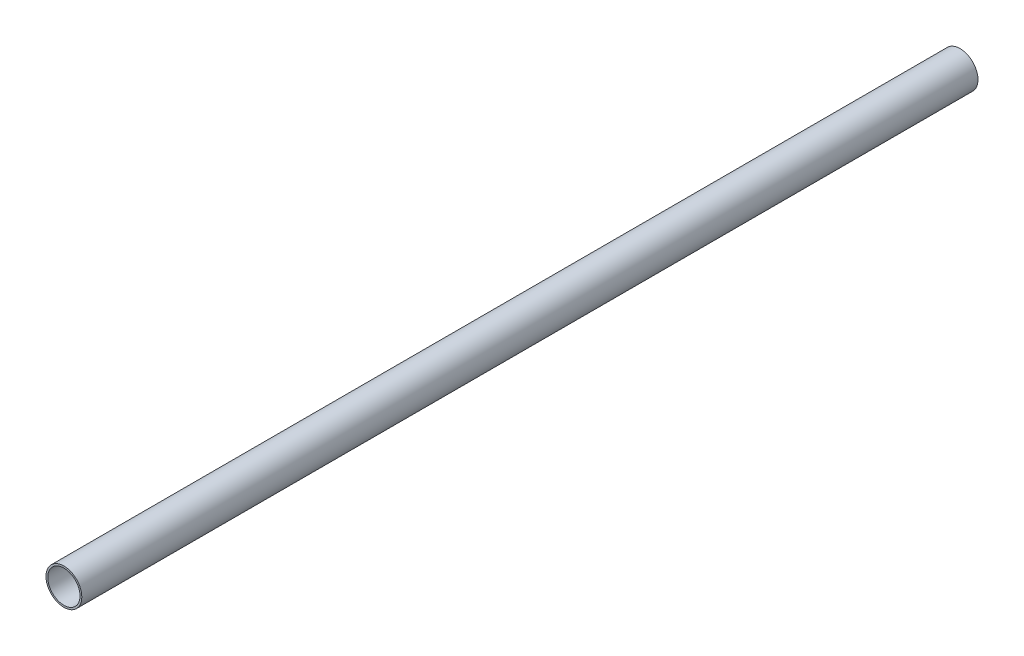
SolidWorks part; units mm, degrees
material "Thornel Mat VMA"
ref_plane "Front Plane" through (0, 0, 0) normal (0, 0, 1) x (1, 0, 0)
ref_plane "Top Plane" through (0, 0, 0) normal (0, 1, 0) x (1, 0, 0)
ref_plane "Right Plane" through (0, 0, 0) normal (1, 0, 0) x (0, 0, -1)
sketch "Sketch1" plane through (0, 0, 0) normal (0, 0, 1) x (1, 0, 0)
  circle A0 centre (0, 0) radius 10
  circle A1 centre (0, 0) radius 9
  dimension "D1" = 18
  dimension "D2" = 20
extrude "Boss-Extrude1" add sketch "Sketch1" along normal blind 500
sketch "Sketch2" plane through (0, 0, 0) normal (1, 0, 0) x (0, 0, -1)
  line L0 (0, 2.5) -> (-30, 2.5)
  line L1 (0, 11) -> (0, -11) construction
  line L2 (-30, 2.5) -> (-30, -13.1955)
  line L3 (-30, -13.1955) -> (0, -13.1955)
  line L4 (0, -13.1955) -> (0, 2.5)
  line L5 (11, 0) -> (-11, 0) construction
  dimension "D1" = 30
  dimension "D2" = 2.5
